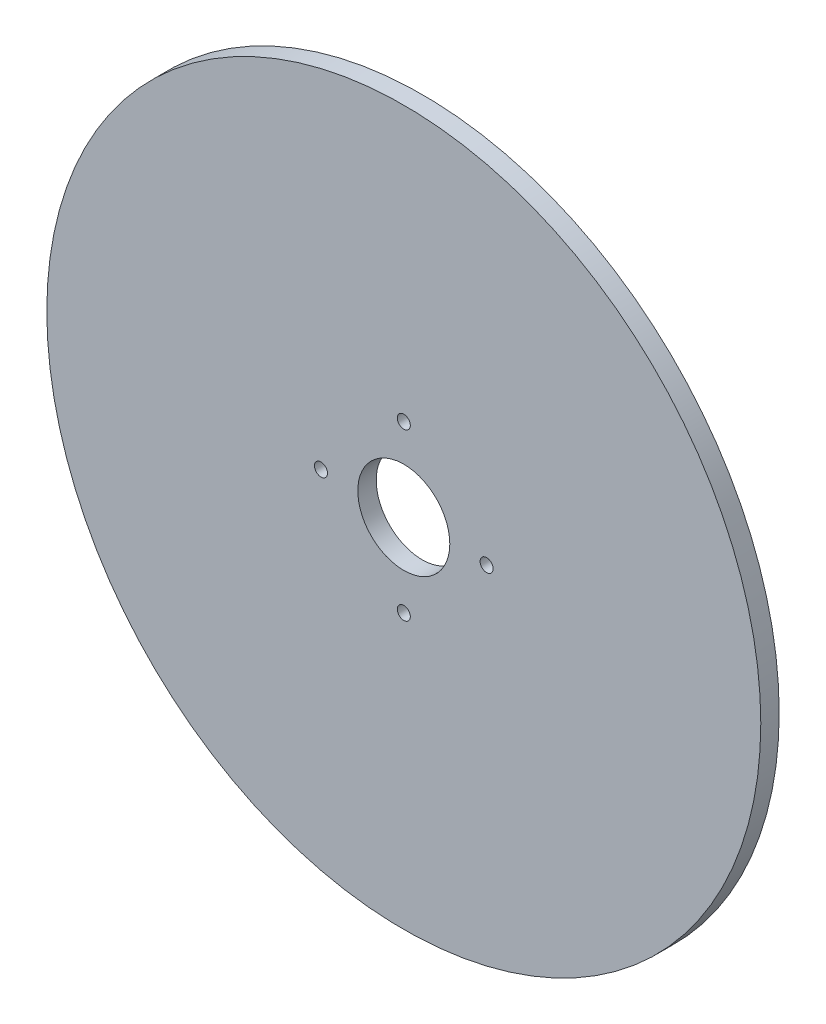
SolidWorks part; units mm, degrees
ref_plane "Front Plane" through (0, 0, 0) normal (0, 0, 1) x (1, 0, 0)
ref_plane "Top Plane" through (0, 0, 0) normal (0, 1, 0) x (1, 0, 0)
ref_plane "Right Plane" through (0, 0, 0) normal (1, 0, 0) x (0, 0, -1)
sketch "Sketch1" plane through (0, 0, 0) normal (0, 0, 1) x (1, 0, 0)
  line L0 (0, 28.575) -> (0, -28.575) construction
  line L1 (-28.575, 0) -> (28.575, 0) construction
  circle A0 centre (0, 0) radius 15.875
  circle A1 centre (0, 0) radius 123.19
  circle A2 centre (0, 28.575) radius 2.25
  circle A3 centre (-28.575, 0) radius 2.25
  circle A4 centre (28.575, 0) radius 2.25
  circle A5 centre (0, -28.575) radius 2.25
  point P7 (0, 0)
  point P11 (0, 0)
  dimension "D1" = 246.38
  dimension "D2" = 31.75
  dimension "D3" = 57.15
  dimension "D4" = 4.5
extrude "Boss-Extrude1" add sketch "Sketch1" along normal blind 6.35
